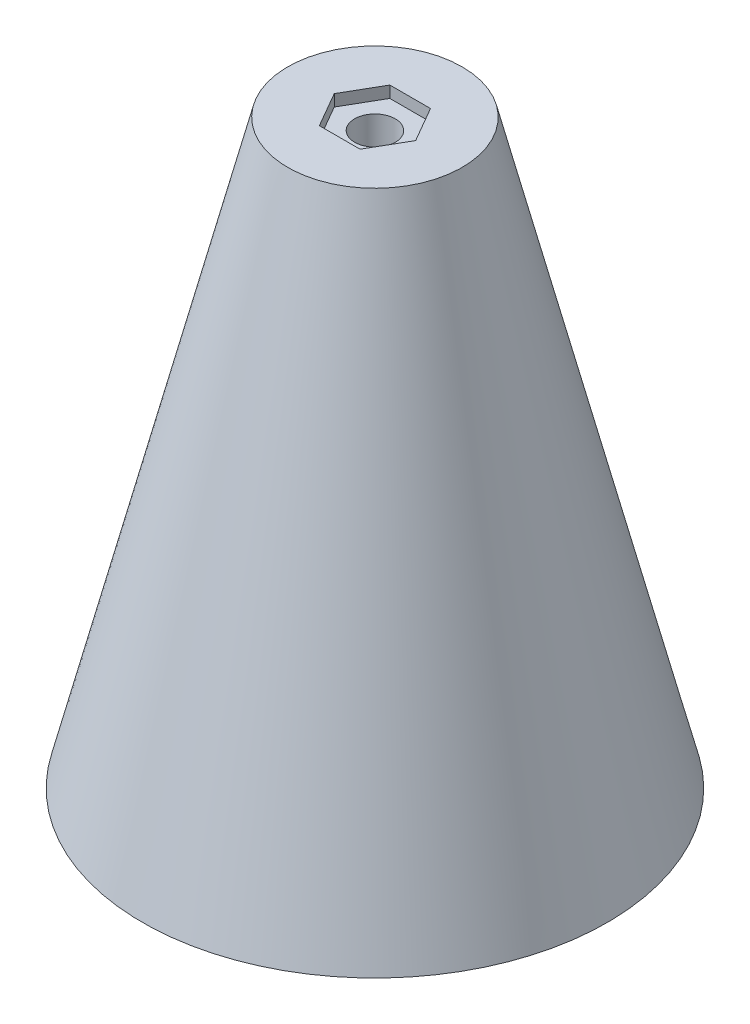
SolidWorks part; units mm, degrees
ref_plane "前视基准面" through (0, 0, 0) normal (0, 0, 1) x (1, 0, 0)
ref_plane "上视基准面" through (0, 0, 0) normal (0, 1, 0) x (1, 0, 0)
ref_plane "右视基准面" through (0, 0, 0) normal (1, 0, 0) x (0, 0, -1)
other "Configuration Table"
sketch "草图3" plane through (0, 0, 0) normal (1, 0, 0) x (0, 0, -1)
  line L0 (-7.5, 0) -> (0, 0)
  line L1 (0, 0) -> (0, -4)
  line L2 (0, -4) -> (-4.5, -4)
  line L3 (-4.5, -4) -> (-16, -50)
  line L4 (-16, -50) -> (-20, -50)
  line L5 (-20, -50) -> (-7.5, 0)
  line L6 (0, 28.4507) -> (0, 37.5487) construction
  dimension "D1" = 4
  dimension "D2" = 4
  dimension "D3" = 50
  dimension "D4" = 7.5
  dimension "D5" = 20
revolve "旋转1" add sketch "草图3" angle 360 about L6
sketch "草图4" plane through (0, 0, 0) normal (0, 1, 0) x (1, 0, 0)
  circle A0 centre (0, 0) radius 1.75
  dimension "D1" = 3.5
extrude "切除-拉伸1" cut sketch "草图4" against normal blind 10 contours A0
sketch "草图5" plane through (0, 0, 0) normal (0, 1, 0) x (1, 0, 0)
  line L1 (3.5, 0) -> (1.75, 3.0311)
  line L2 (1.75, 3.0311) -> (-1.75, 3.0311)
  line L3 (-1.75, 3.0311) -> (-3.5, 0)
  line L4 (-3.5, 0) -> (-1.75, -3.0311)
  line L5 (-1.75, -3.0311) -> (1.75, -3.0311)
  line L6 (1.75, -3.0311) -> (3.5, 0)
  circle A0 centre (0, 0) radius 3.0311 construction
  dimension "D1" = 3.5
extrude "切除-拉伸2" cut sketch "草图5" against normal blind 1
chamfer "倒角1" distance 0.5 angle 45 1 edges at (0, -4, 1.75)
